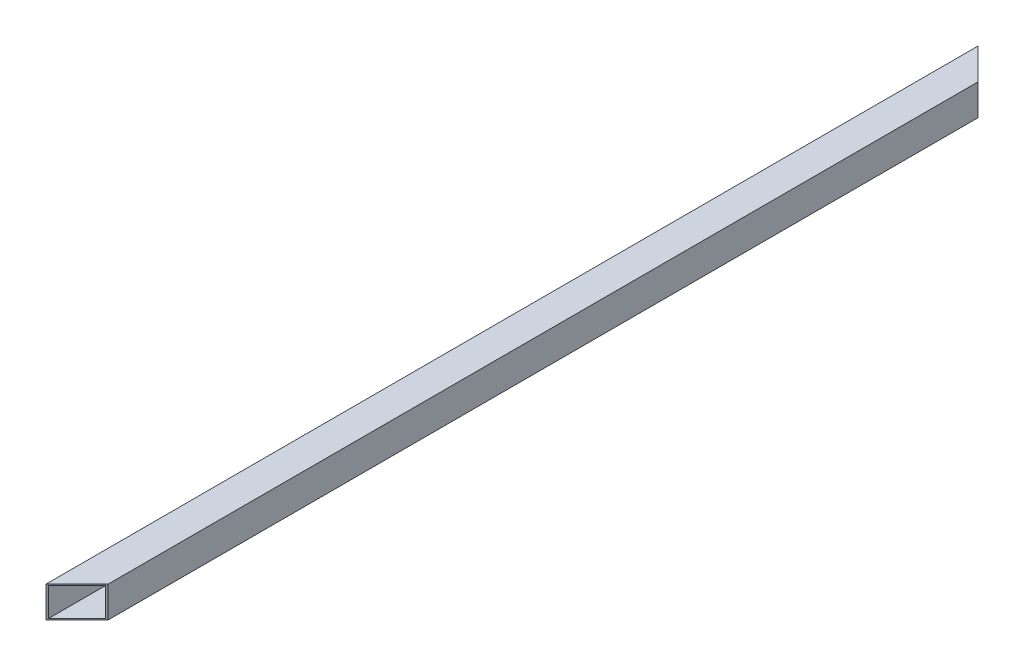
SolidWorks part; units mm, degrees
ref_plane "Alzado" through (0, 0, 0) normal (0, 0, 1) x (1, 0, 0)
ref_plane "Planta" through (0, 0, 0) normal (0, 1, 0) x (1, 0, 0)
ref_plane "Vista lateral" through (0, 0, 0) normal (1, 0, 0) x (0, 0, -1)
sketch "Croquis1" plane through (0, 0, 0) normal (0, 0, 1) x (1, 0, 0)
  line L1 (-69.6345, 59.7691) -> (30.3655, 59.7691)
  line L2 (-69.6345, 59.7691) -> (-69.6345, -40.2309)
  line L3 (-69.6345, -40.2309) -> (30.3655, -40.2309)
  line L4 (30.3655, 59.7691) -> (30.3655, -40.2309)
  line L5 (-65.6345, 55.7691) -> (26.3655, 55.7691)
  line L6 (-65.6345, 55.7691) -> (-65.6345, -36.2309)
  line L7 (-65.6345, -36.2309) -> (26.3655, -36.2309)
  line L8 (26.3655, 55.7691) -> (26.3655, -36.2309)
  dimension "D1" = 100
  dimension "D2" = 100
  dimension "D3" = 4
  dimension "D4" = 4
  dimension "D5" = 4
  dimension "D6" = 4
extrude "Saliente-Extruir3" add sketch "Croquis1" along normal blind 3000
sketch "Croquis2" plane through (0, 59.7691, 0) normal (0, 1, 0) x (1, 0, 0)
  line L0 (-69.6345, 0) -> (30.3655, -100)
  line L1 (30.3655, -3000) -> (30.3655, 0) construction
  line L2 (30.3655, -100) -> (30.3655, 0)
  line L3 (30.3655, 0) -> (-69.6345, 0)
extrude "Cortar-Extruir1" cut sketch "Croquis2" against normal blind 390 and the other way blind 409
sketch "Croquis3" plane through (0, 59.7691, 0) normal (0, 1, 0) x (1, 0, 0)
  line L0 (-69.6345, -3000) -> (30.3655, -2900)
  line L1 (30.3655, -3000) -> (30.3655, -100) construction
  line L2 (30.3655, -2900) -> (30.3655, -3000)
  line L3 (30.3655, -3000) -> (-69.6345, -3000)
extrude "Cortar-Extruir2" cut sketch "Croquis3" along normal blind 232 and the other way blind 271
